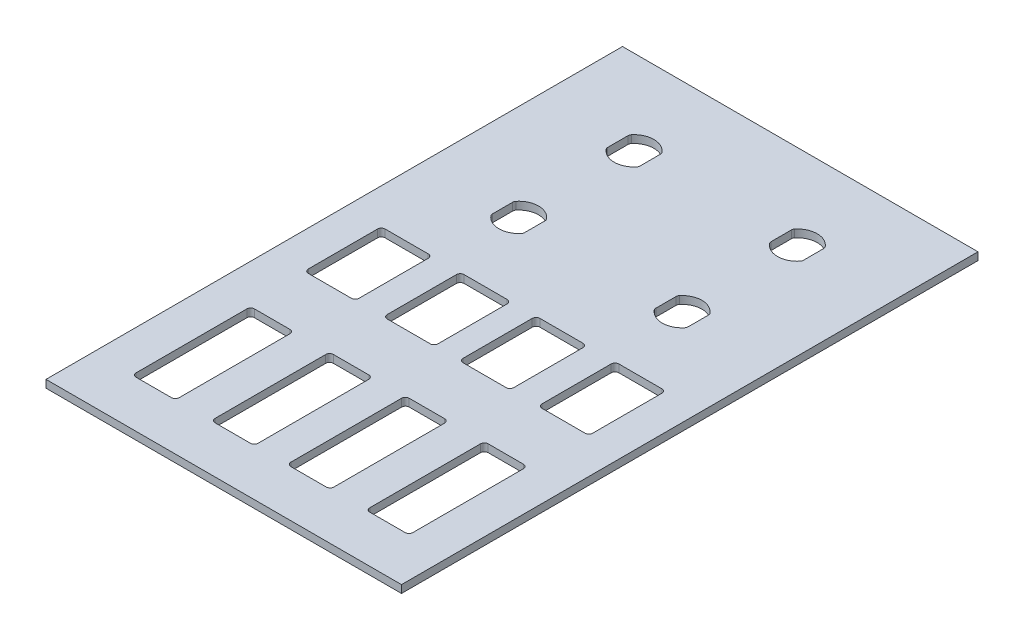
SolidWorks part; units mm, degrees
ref_plane "Ebene vorne" through (0, 0, 0) normal (0, 0, 1) x (1, 0, 0)
ref_plane "Ebene oben" through (0, 0, 0) normal (0, 1, 0) x (1, 0, 0)
ref_plane "Ebene rechts" through (0, 0, 0) normal (1, 0, 0) x (0, 0, -1)
sketch "Skizze1" plane through (0, 0, 0) normal (0, 1, 0) x (1, 0, 0)
  line L1 (0, 0) -> (92.5, 0)
  line L2 (0, 0) -> (0, 150)
  line L3 (0, 150) -> (92.5, 150)
  line L4 (92.5, 0) -> (92.5, 150)
  dimension "D1" = 92.5
  dimension "D2" = 150
extrude "Aufsatz-Linear austragen1" add sketch "Skizze1" along normal blind 2
sketch "Skizze2" plane through (0, 2, 0) normal (0, 1, 0) x (1, 0, 0)
  line L0 (92.5, 150) -> (0, 150) construction
  line L1 (0, 150) -> (0, 0) construction
  line L2 (25, 133.15) -> (25, 122.85) construction
  line L3 (20.8, 130.9804) -> (20.8, 125.0196)
  line L4 (29.2, 130.9804) -> (29.2, 125.0196)
  arc A0 (20.8, 125.0196) -> (29.2, 125.0196) centre (25, 128) ccw
  arc A1 (29.2, 130.9804) -> (20.8, 130.9804) centre (25, 128) ccw
  dimension "D3" = 10.3
  dimension "D1" = 22
  dimension "D2" = 25
  dimension "D4" = 8.4
extrude "Schnitt-Linear austragen1" cut sketch "Skizze2" against normal through all
ref_plane "Ebene1" through (46.25, 0, 0) normal (1, 0, 0) x (0, 0, -1)
pattern_linear "Lineares Muster1" count 2 spacing 30 along (0, 0, 1) of "Schnitt-Linear austragen1"
mirror "Spiegeln1" about plane through (46.25, 0, 0) normal (1, 0, 0) of "Lineares Muster1", "Schnitt-Linear austragen1"
sketch "Skizze3" plane through (0, 2, 0) normal (0, 1, 0) x (1, 0, 0)
  line L0 (46.25, 0) -> (46.25, 150) construction
  line L1 (0, 0) -> (92.5, 0) construction
  line L2 (92.5, 150) -> (0, 150) construction
  line L3 (0, 150) -> (0, 0) construction
  line L4 (9.25, 58) -> (22.45, 58)
  line L5 (9.25, 58) -> (9.25, 78)
  line L6 (9.25, 78) -> (22.45, 78)
  line L7 (22.45, 58) -> (22.45, 78)
  line L8 (49.515, 58) -> (49.515, 78)
  line L13 (29.785, 58) -> (42.985, 58)
  line L14 (29.785, 58) -> (29.785, 78)
  line L15 (29.785, 78) -> (42.985, 78)
  line L16 (42.985, 58) -> (42.985, 78)
  line L17 (62.715, 78) -> (49.515, 78)
  line L18 (62.715, 58) -> (62.715, 78)
  line L19 (62.715, 58) -> (49.515, 58)
  line L20 (70.05, 58) -> (70.05, 78)
  line L21 (83.25, 78) -> (70.05, 78)
  line L22 (83.25, 58) -> (83.25, 78)
  line L23 (83.25, 58) -> (70.05, 58)
  dimension "D1" = 13.2
  dimension "D2" = 20
  dimension "D3" = 9.25
  dimension "D4" = 58
  dimension "D5" = 13.2
  dimension "D6" = 20
  dimension "D7" = 7.335
extrude "Schnitt-Linear austragen2" cut sketch "Skizze3" against normal through all
fillet "Verrundung1" radius 1 16 edges at (49.515, 1, -58) (70.05, 1, -58) (62.715, 1, -58) (83.25, 1, -58) (49.515, 1, -78) (70.05, 1, -78) (83.25, 1, -78) (62.715, 1, -78) (42.985, 1, -78) (29.785, 1, -78) (29.785, 1, -58) (42.985, 1, -58) (22.45, 1, -58) (9.25, 1, -58) (22.45, 1, -78) (9.25, 1, -78)
fillet "Verrundung2" radius 1 16 edges at (20.8, 1, -125.0196) (63.3, 1, -125.0196) (63.3, 1, -95.0196) (20.8, 1, -95.0196) (71.7, 1, -95.0196) (29.2, 1, -125.0196) (29.2, 1, -95.0196) (71.7, 1, -125.0196) (63.3, 1, -130.9804) (63.3, 1, -100.9804) (20.8, 1, -100.9804) (29.2, 1, -100.9804) (71.7, 1, -100.9804) (71.7, 1, -130.9804) (29.2, 1, -130.9804) (20.8, 1, -130.9804)
sketch "Skizze4" plane through (0, 2, 0) normal (0, 1, 0) x (1, 0, 0)
  line L0 (46.25, 0) -> (46.25, 150) construction
  line L1 (0, 0) -> (92.5, 0) construction
  line L2 (92.5, 150) -> (0, 150) construction
  line L3 (15.85, 78) -> (15.85, 0) construction
  line L4 (10.25, 12.2) -> (21.45, 12.2)
  line L5 (10.25, 12.2) -> (10.25, 43)
  line L6 (10.25, 43) -> (21.45, 43)
  line L7 (21.45, 12.2) -> (21.45, 43)
  line L8 (21.45, 78) -> (10.25, 78) construction
  line L9 (36.385, 78) -> (36.385, 0) construction
  line L10 (41.985, 78) -> (30.785, 78) construction
  line L11 (10.25, 58) -> (21.45, 58) construction
  line L12 (30.785, 12.2) -> (41.985, 12.2)
  line L13 (30.785, 12.2) -> (30.785, 43)
  line L14 (30.785, 43) -> (41.985, 43)
  line L15 (41.985, 12.2) -> (41.985, 43)
  dimension "D1" = 30.8
  dimension "D2" = 11.2
  dimension "D3" = 11.2
  dimension "D4" = 30.8
  dimension "D5" = 15
extrude "Schnitt-Linear austragen3" cut sketch "Skizze4" against normal through all
mirror "Spiegeln2" about plane through (46.25, 0, 0) normal (1, 0, 0) of "Schnitt-Linear austragen3"
fillet "Verrundung3" radius 1 16 edges at (10.25, 1, -12.2) (30.785, 1, -12.2) (50.515, 1, -12.2) (71.05, 1, -12.2) (21.45, 1, -12.2) (41.985, 1, -12.2) (61.715, 1, -12.2) (82.25, 1, -12.2) (82.25, 1, -43) (61.715, 1, -43) (41.985, 1, -43) (21.45, 1, -43) (71.05, 1, -43) (50.515, 1, -43) (30.785, 1, -43) (10.25, 1, -43)
